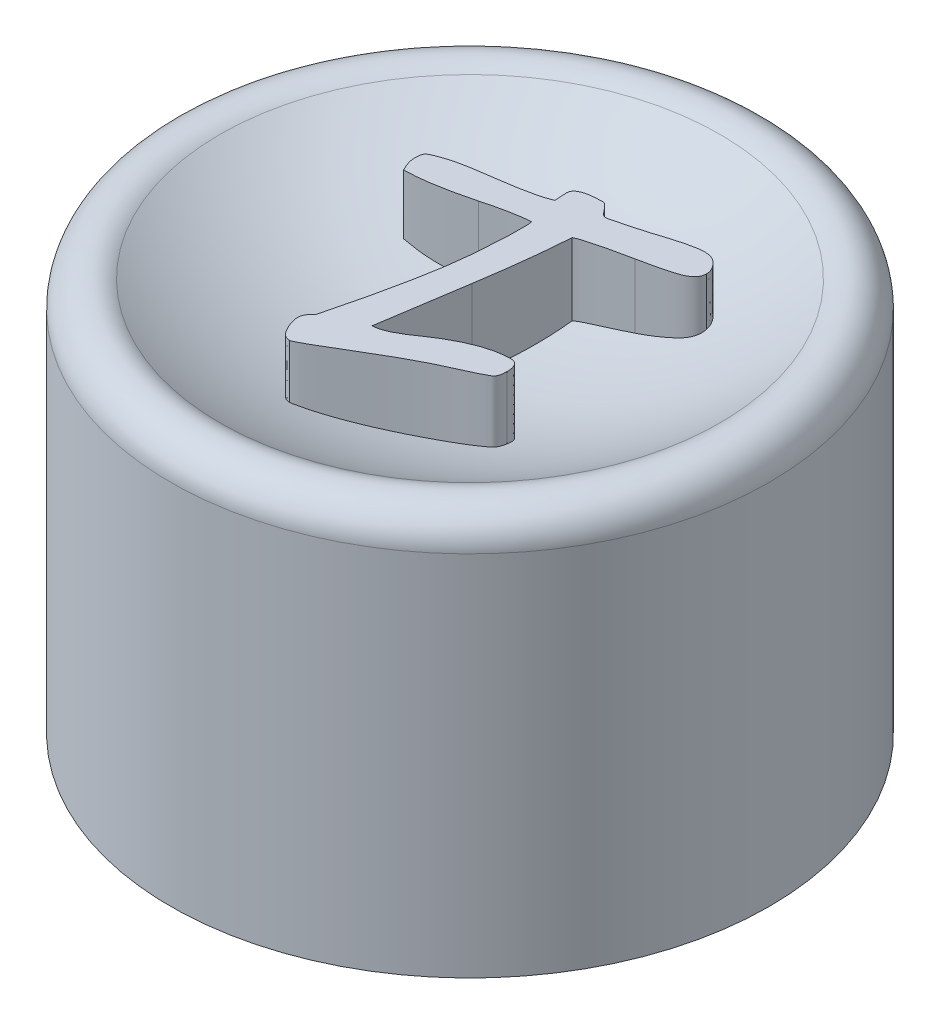
SolidWorks part; units mm, degrees
ref_plane "Front Plane" through (0, 0, 0) normal (0, 0, 1) x (1, 0, 0)
ref_plane "Top Plane" through (0, 0, 0) normal (0, 1, 0) x (1, 0, 0)
ref_plane "Right Plane" through (0, 0, 0) normal (1, 0, 0) x (0, 0, -1)
sketch "Sketch1" plane through (0, 0, 0) normal (0, 0, 1) x (1, 0, 0)
  line L0 (0, 0) -> (0, -66.4851) construction
  line L1 (55, 0) -> (-55, 0) construction
  line L2 (-1.5494, 0) -> (-1.5494, 3.048)
  line L3 (-1.5494, 3.048) -> (-0.762, 3.048)
  line L4 (-0.762, 3.048) -> (-0.762, 4.064)
  line L5 (-0.762, 4.064) -> (0, 4.064)
  line L6 (0, -55) -> (0, 55) construction
  line L7 (0, 4.064) -> (0, 5.08)
  line L8 (-4.7625, 5.842) -> (-4.7625, 0)
  line L9 (-4.7625, 0) -> (-3.4925, 0)
  line L10 (-3.4925, 0) -> (-3.4925, 4.064)
  line L11 (-3.4925, 4.064) -> (-2.0574, 4.064)
  line L12 (-2.0574, 4.064) -> (-2.0574, 0)
  line L13 (-2.0574, 0) -> (-1.5494, 0)
  line L14 (0, 5.08) -> (3.3062, 5.08) construction
  arc A0 (-4.7625, 5.842) -> (-3.976, 6.2669) centre (-4.2545, 5.842) cw
  arc A1 (-3.976, 6.2669) -> (0, 5.08) centre (0, 12.3333) ccw
  dimension "D4" = 1.524
  dimension "D5" = 6.35
  dimension "D9" = 0.508
  dimension "D1" = 9.525
  dimension "D2" = 3.0988
  dimension "D3" = 3.048
  dimension "D6" = 0.508
  dimension "D7" = 1.016
  dimension "D8" = 1.27
  dimension "D10" = 5.08
revolve "Revolve1" add sketch "Sketch1" angle 360 about L0
ref_plane "Plane1" through (0, 6.35, 0) normal (0, 1, 0) x (-1, 0, 0)
sketch "Sketch3" plane through (0, 6.35, 0) normal (0, 1, 0) x (-1, 0, 0)
  line L0 (-2.3812, -2.032) -> (2.3813, -2.032) construction
  line L1 (0, 0) -> (0, -7.9672) construction
  line L2 (0, 3.4925) -> (0, -3.4925) construction
  line L3 (3.4925, 0) -> (-3.4925, 0) construction
  text T0 "1" font "Segoe Print" height 4.7625
  dimension "D1" = 2.032
  dimension "D2" = 4.7625
extrude "Boss-Extrude1" add sketch "Sketch3" against normal up to surface (0.8897 mm away)
